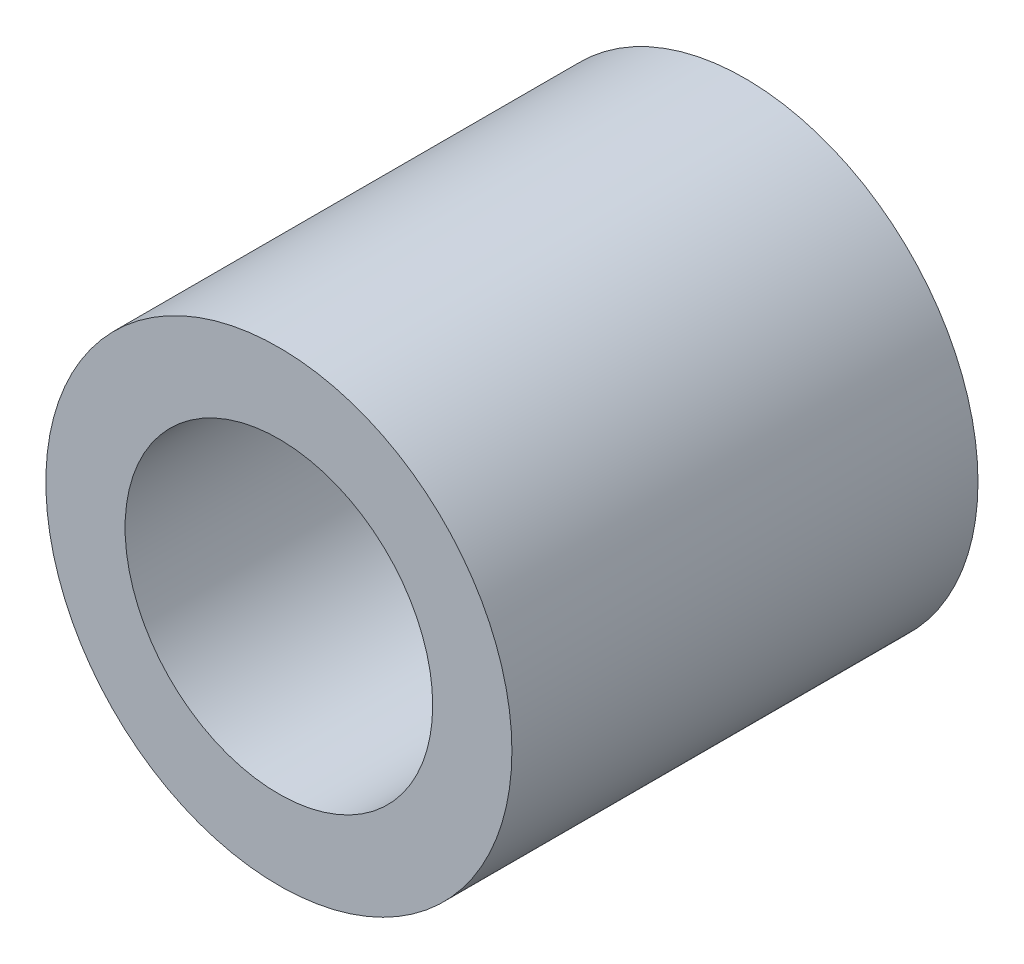
SolidWorks part; units mm, degrees
ref_plane "前视基准面" through (0, 0, 0) normal (0, 0, 1) x (1, 0, 0)
ref_plane "上视基准面" through (0, 0, 0) normal (0, 1, 0) x (1, 0, 0)
ref_plane "右视基准面" through (0, 0, 0) normal (1, 0, 0) x (0, 0, -1)
other "Configuration Table"
sketch "草图1" plane through (0, 0, 0) normal (0, 0, 1) x (1, 0, 0)
  circle A0 centre (0, 0) radius 16.5
  circle A1 centre (0, 0) radius 25
  dimension "D1" = 33
  dimension "D2" = 50
extrude "凸台-拉伸1" add sketch "草图1" along normal blind 50
